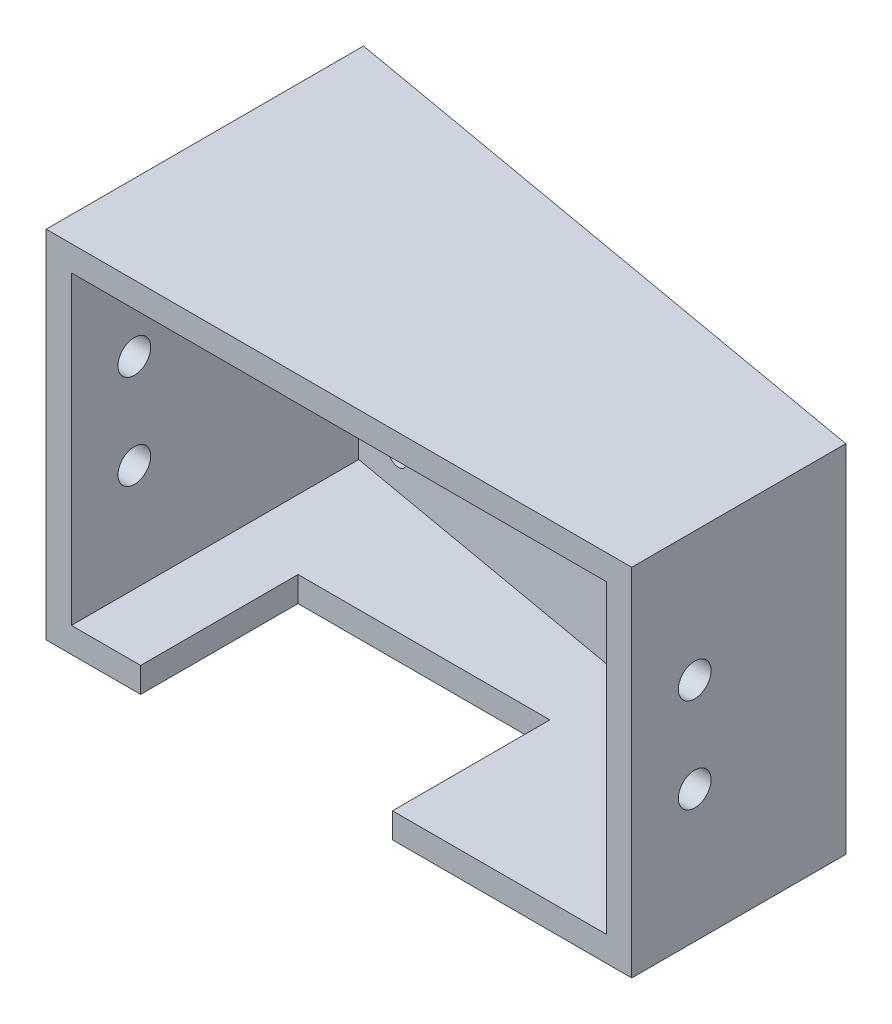
SolidWorks part; units mm, degrees
ref_plane "Front Plane" through (0, 0, 0) normal (0, 0, 1) x (1, 0, 0)
ref_plane "Top Plane" through (0, 0, 0) normal (0, 1, 0) x (1, 0, 0)
ref_plane "Right Plane" through (0, 0, 0) normal (1, 0, 0) x (0, 0, -1)
sketch "Sketch1" plane through (0, 0, 0) normal (0, 1, 0) x (1, 0, 0)
  line L0 (0, 43.18) -> (0, 64.006)
  line L1 (0, 0) -> (118.11, 0)
  line L2 (0, 0) -> (0, 43.18)
  line L4 (118.11, 0) -> (118.11, 43.18)
  line L5 (0, 64.006) -> (118.11, 43.18)
  dimension "D1" = 118.11
  dimension "D2" = 43.18
  dimension "D3" = 10
extrude "Boss-Extrude1" add sketch "Sketch1" along normal blind 5.08
sketch "Sketch2" plane through (0, 0, 0) normal (0, -1, 0) x (1, 0, 0)
  line L1 (5.08, -5.08) -> (5.08, -57.9519)
  line L2 (5.08, -57.9519) -> (113.03, -38.9174)
  line L3 (113.03, -38.9174) -> (113.03, -5.08)
  line L4 (0, 0) -> (118.11, 0) construction
  line L5 (0, 0) -> (0, -64.006) construction
  line L8 (118.11, 0) -> (113.03, 0)
  line L9 (0, 0) -> (0, -64.006)
  line L10 (0, -64.006) -> (118.11, -43.18)
  line L11 (118.11, -43.18) -> (118.11, 0)
  line L12 (113.03, -5.08) -> (5.08, -5.08) construction
  line L13 (5.08, -5.08) -> (5.08, 0)
  line L14 (113.03, -5.08) -> (113.03, 0)
  line L15 (5.08, 0) -> (0, 0)
  line L16 (118.11, 0) -> (0, 0) construction
  dimension "D2" = 5.08
extrude "Boss-Extrude2" add sketch "Sketch2" along normal blind 61.595
sketch "Sketch3" plane through (0, -61.595, 0) normal (0, -1, 0) x (1, 0, 0)
  line L0 (0, -64.006) -> (118.11, -43.18) construction
  line L2 (118.11, 0) -> (113.03, 0) construction
  line L3 (5.08, 0) -> (0, 0) construction
  line L4 (69.85, 0) -> (69.85, -31.75)
  line L5 (69.85, -31.75) -> (19.05, -31.75)
  line L6 (0, -64.006) -> (118.11, -43.18)
  line L7 (118.11, -43.18) -> (118.11, 0)
  line L8 (118.11, 0) -> (0, 0)
  line L9 (118.11, 0) -> (0, 0)
  line L10 (0, 0) -> (0, -64.006)
  line L11 (118.11, 0) -> (0, 0)
  line L12 (19.05, -31.75) -> (19.05, 0)
  line L16 (118.11, 0) -> (118.11, -43.18) construction
  line M7 (118.11, -43.18) -> (118.11, 0)
  line M8 (118.11, 0) -> (113.03, 0)
  line M9 (113.03, 0) -> (113.03, -38.9174)
  line M10 (113.03, -38.9174) -> (5.08, -57.9519)
  line M11 (5.08, -57.9519) -> (5.08, 0)
  line M13 (0, 0) -> (0, -64.006)
  line M14 (0, -64.006) -> (118.11, -43.18)
  line M15 (5.08, 0) -> (0, 0)
  dimension "D1" = 50.8
  dimension "D2" = 31.75
  dimension "D3" = 19.05
extrude "Boss-Extrude3" add sketch "Sketch3" along normal blind 5.08 contours L5 L12 L11 L8 L4 M11 M10 M9 | M14 M7 M8 M9 M10 M11 M15 M13
sketch "Sketch4" plane through (0, 0, 0) normal (-1, 0, 0) x (0, 0, 1)
  line L1 (0, 5.08) -> (0, -66.675) construction
  line L2 (0, 5.08) -> (-64.006, 5.08) construction
  circle A0 centre (-12.7, -20.955) radius 3.302
  circle A1 centre (-12.7, -40.005) radius 3.302
  dimension "D2" = 12.7
  dimension "D3" = 6.604
  dimension "D1" = 26.035
  dimension "D5" = 19.05
  dimension "D4" = 2
extrude "Cut-Extrude1" cut sketch "Sketch4" against normal through all
sketch "Sketch5" plane through (10.9457, 0, -62.076) normal (0.1736, 0, -0.9848) x (-0.9848, 0, -0.1736)
  line L0 (11.1145, 5.08) -> (11.1145, -66.675) construction
  line L1 (-93.3015, -6.985) -> (-48.8515, -6.985) construction
  line L2 (-48.8515, 5.08) -> (-48.8515, -66.675) construction
  line L3 (-48.8515, -6.985) -> (-4.4015, -6.985) construction
  line L4 (-108.8175, -30.7975) -> (11.1145, -30.7975) construction
  line L5 (-108.8175, 5.08) -> (-108.8175, -66.675) construction
  line L6 (11.1145, 5.08) -> (-108.8175, 5.08) construction
  line L7 (-93.3015, -6.985) -> (-93.3015, -30.7975) construction
  line L8 (-93.3015, -30.7975) -> (-93.3015, -54.61) construction
  circle A1 centre (-93.3015, -6.985) radius 2.667
  circle A3 centre (-93.3015, -54.61) radius 2.667
  circle A4 centre (-4.4015, -6.985) radius 2.667
  circle A5 centre (-4.4015, -54.61) radius 2.667
  point P4 (-48.8515, 5.08)
  dimension "D1" = 47.625
  dimension "D2" = 88.9
  dimension "D3" = 5.334
  dimension "D4" = 5.334
extrude "Cut-Extrude2" cut sketch "Sketch5" against normal blind 5.08
